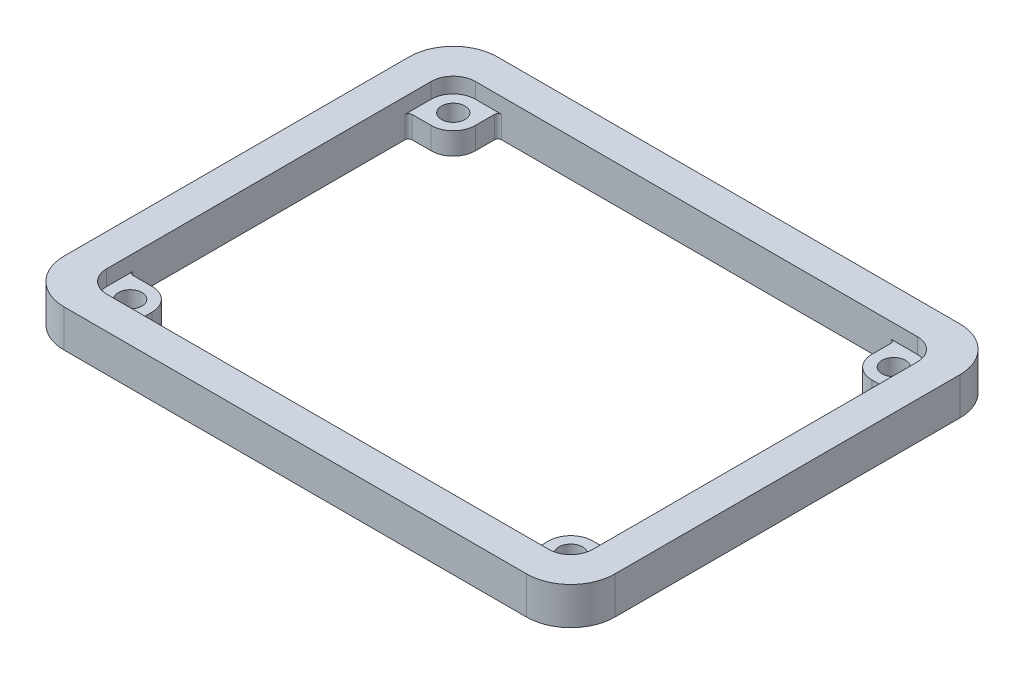
SolidWorks part; units mm, degrees
material "ABS"
ref_plane "Front Plane" through (0, 0, 0) normal (0, 0, 1) x (1, 0, 0)
ref_plane "Top Plane" through (0, 0, 0) normal (0, 1, 0) x (1, 0, 0)
ref_plane "Right Plane" through (0, 0, 0) normal (1, 0, 0) x (0, 0, -1)
sketch "Sketch1" plane through (0, 0, 0) normal (0, 1, 0) x (1, 0, 0)
  line L0 (-27, -22) -> (-27, -24.6)
  line L1 (-30, -22) -> (30, -22) construction
  line L2 (-30, -22) -> (-30, 22) construction
  line L3 (-30, 22) -> (30, 22) construction
  line L4 (30, -22) -> (30, 22) construction
  line L5 (-30, -22) -> (30, 22) construction
  line L6 (-30, 22) -> (30, -22) construction
  line L7 (-31.5, -29.5) -> (31.5, -29.5)
  line L8 (-37.5, -23.5) -> (-37.5, 23.5)
  line L9 (-31.5, 29.5) -> (31.5, 29.5)
  line L10 (37.5, -23.5) -> (37.5, 23.5)
  line L11 (30.8386, -23.3626) -> (-30.8386, 23.3626) construction
  line L12 (-27, 29.4) -> (-27, 29.5)
  line L17 (0, 0) -> (0, 29.5) construction
  line L18 (30.8386, 23.3626) -> (-30.8386, -23.3626) construction
  line L19 (27, -22) -> (27, -24.6)
  line L20 (30, -19) -> (32.6, -19)
  line L21 (30, 19) -> (32.6, 19)
  line L22 (27, 22) -> (27, 24.6)
  line L23 (-27, 22) -> (-27, 24.6)
  line L24 (-30, 19) -> (-32.6, 19)
  line L25 (-30, -19) -> (-32.6, -19)
  line L29 (-27.2, 29.4) -> (27.2, 29.4) construction
  line L33 (33.1, -18.5) -> (33.1, 18.5)
  line L35 (-33.1, -18.5) -> (-33.1, 18.5)
  line L36 (0, 0) -> (37.5, 0) construction
  line L37 (30.8221, 23.3726) -> (-30.8221, -23.3726) construction
  line L38 (26.5, -25.1) -> (-26.5, -25.1)
  line L39 (27, 29.4) -> (27, 29.5)
  line L40 (26.5, 25.1) -> (-26.5, 25.1)
  line L41 (-30, -23.6) -> (30, 23.6) construction
  line L42 (-30, 23.6) -> (30, -23.6) construction
  line L43 (30.8221, -23.3726) -> (-30.8221, 23.3726) construction
  circle A0 centre (-30, 22) radius 1.6
  circle A1 centre (30, 22) radius 1.6
  circle A2 centre (30, -22) radius 1.6
  circle A3 centre (-30, -22) radius 1.6
  arc A8 (27, 22) -> (30, 19) centre (30, 22) ccw
  arc A9 (30, -19) -> (27, -22) centre (30, -22) ccw
  arc A10 (-27, -22) -> (-30, -19) centre (-30, -22) ccw
  arc A11 (-30, 19) -> (-27, 22) centre (-30, 22) ccw
  arc A12 (-31.5, -29.5) -> (-37.5, -23.5) centre (-31.5, -23.5) cw
  arc A13 (31.5, -29.5) -> (37.5, -23.5) centre (31.5, -23.5) ccw
  arc A14 (31.5, 29.5) -> (37.5, 23.5) centre (31.5, 23.5) cw
  arc A15 (-37.5, 23.5) -> (-31.5, 29.5) centre (-31.5, 23.5) cw
  arc A16 (-33.1, -18.5) -> (-32.6, -19) centre (-32.6, -18.5) ccw
  arc A17 (-26.5, -25.1) -> (-27, -24.6) centre (-26.5, -24.6) cw
  arc A18 (26.5, -25.1) -> (27, -24.6) centre (26.5, -24.6) ccw
  arc A19 (33.1, -18.5) -> (32.6, -19) centre (32.6, -18.5) cw
  arc A20 (32.6, 19) -> (33.1, 18.5) centre (32.6, 18.5) cw
  arc A21 (27, 24.6) -> (26.5, 25.1) centre (26.5, 24.6) ccw
  arc A22 (-33.1, 18.5) -> (-32.6, 19) centre (-32.6, 18.5) cw
  arc A23 (-27, 24.6) -> (-26.5, 25.1) centre (-26.5, 24.6) cw
  point P0 (0, 0)
  point P10 (0, 0)
  point P15 (0, 0)
  point P52 (0, 0)
  point P60 (-37.5, -29.5)
  point P70 (37.5, 29.5)
  point P73 (-37.5, 29.5)
  dimension "D3" = 3.2
  dimension "D6" = 6
  dimension "D7" = 0.5
  dimension "D1" = 60
  dimension "D2" = 44
  dimension "D4" = 75
  dimension "D5" = 59
extrude "Boss-Extrude1" add sketch "Sketch1" along normal blind 3
sketch "Sketch2" plane through (0, 3, 0) normal (0, 1, 0) x (1, 0, 0)
  line L1 (-30.1, -25.1) -> (30.1, -25.1)
  line L2 (-33.1, -22.1) -> (-33.1, 22.1)
  line L3 (-30.1, 25.1) -> (30.1, 25.1)
  line L4 (33.1, -22.1) -> (33.1, 22.1)
  line L5 (-33.1, -25.1) -> (33.1, 25.1) construction
  line L6 (-33.1, 25.1) -> (33.1, -25.1) construction
  line L7 (-31.5, -29.5) -> (31.5, -29.5)
  line L8 (-37.5, -23.5) -> (-37.5, 23.5)
  line L9 (-31.5, 29.5) -> (31.5, 29.5)
  line L10 (37.5, -23.5) -> (37.5, 23.5)
  line L11 (-37.5, -29.5) -> (37.5, 29.5) construction
  line L12 (-37.5, 29.5) -> (37.5, -29.5) construction
  line L13 (37.5, -23.5) -> (37.5, 23.5) construction
  line L14 (-31.5, -29.5) -> (31.5, -29.5) construction
  arc A0 (-30.1, -25.1) -> (-33.1, -22.1) centre (-30.1, -22.1) cw
  arc A1 (30.1, -25.1) -> (33.1, -22.1) centre (30.1, -22.1) ccw
  arc A2 (30.1, 25.1) -> (33.1, 22.1) centre (30.1, 22.1) cw
  arc A3 (-33.1, 22.1) -> (-30.1, 25.1) centre (-30.1, 22.1) cw
  arc A4 (-31.5, -29.5) -> (-37.5, -23.5) centre (-31.5, -23.5) cw
  arc A5 (31.5, -29.5) -> (37.5, -23.5) centre (31.5, -23.5) ccw
  arc A6 (31.5, 29.5) -> (37.5, 23.5) centre (31.5, 23.5) cw
  arc A7 (-37.5, 23.5) -> (-31.5, 29.5) centre (-31.5, 23.5) cw
  point P0 (0, 0)
  point P18 (0, 0)
  dimension "D3" = 3
  dimension "D4" = 6
  dimension "D1" = 66.2
  dimension "D2" = 50.2
extrude "Boss-Extrude2" add sketch "Sketch2" along normal blind 2.1
equation "\"D4@Sketch1\"=\"D1@Sketch1\"+15"
equation "\"D5@Sketch1\"=\"D2@Sketch1\"+15"
